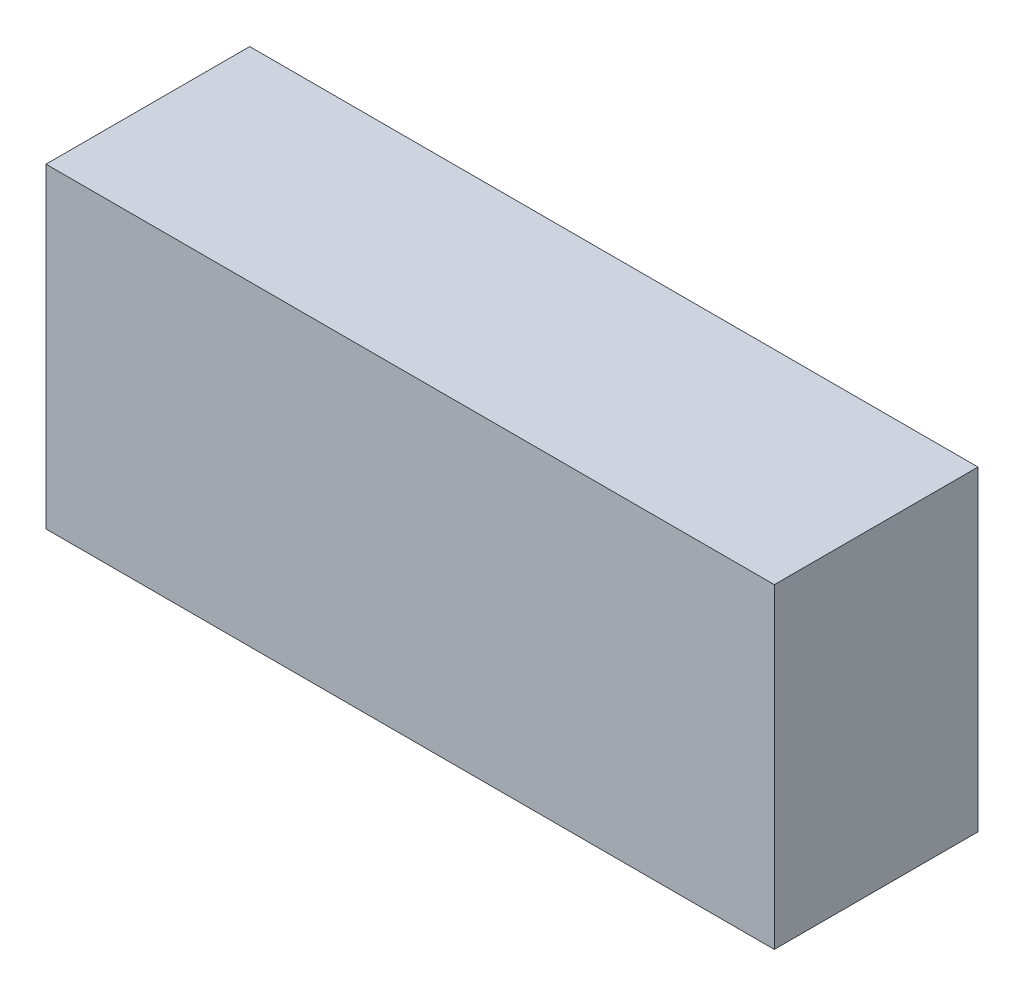
SolidWorks part; units mm, degrees
ref_plane "Front Plane" through (0, 0, 0) normal (0, 0, 1) x (1, 0, 0)
ref_plane "Top Plane" through (0, 0, 0) normal (0, 1, 0) x (1, 0, 0)
ref_plane "Right Plane" through (0, 0, 0) normal (1, 0, 0) x (0, 0, -1)
sketch "Sketch1" plane through (0, 0, 0) normal (0, 0, 1) x (1, 0, 0)
  line L1 (-43.8, -19) -> (43.8, -19)
  line L2 (-43.8, -19) -> (-43.8, 19)
  line L3 (-43.8, 19) -> (43.8, 19)
  line L4 (43.8, -19) -> (43.8, 19)
  line L5 (-43.8, -19) -> (43.8, 19) construction
  line L6 (-43.8, 19) -> (43.8, -19) construction
  point P0 (0, 0)
  dimension "D1" = 87.6
  dimension "D2" = 38
extrude "Boss-Extrude1" add sketch "Sketch1" along normal mid plane 24.5
